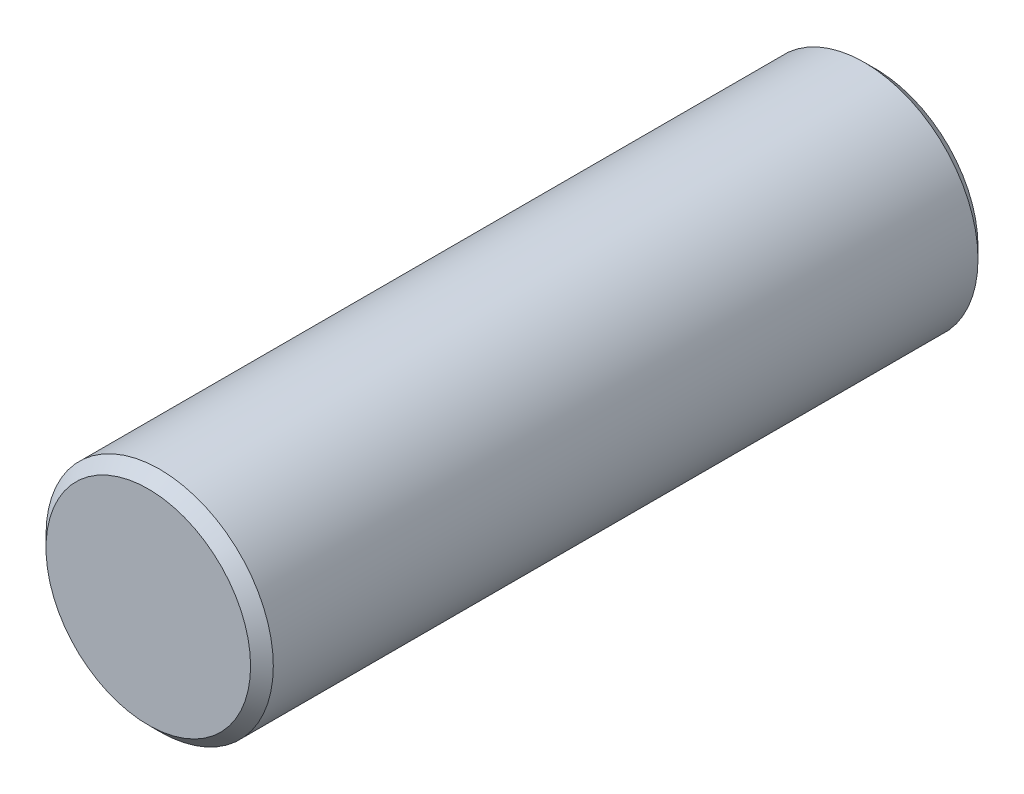
SolidWorks part; units mm, degrees
ref_plane "Front Plane" through (0, 0, 0) normal (0, 0, 1) x (1, 0, 0)
ref_plane "Top Plane" through (0, 0, 0) normal (0, 1, 0) x (1, 0, 0)
ref_plane "Right Plane" through (0, 0, 0) normal (1, 0, 0) x (0, 0, -1)
sketch "Sketch1" plane through (0, 0, 0) normal (0, 0, 1) x (1, 0, 0)
  circle A0 centre (0, 0) radius 2.5
  dimension "D1" = 5
extrude "Boss-Extrude1" add sketch "Sketch1" along normal mid plane 16
chamfer "Chamfer1" distance 0.25 angle 45 2 edges at (2.5, 0, -8) (2.5, 0, 8)
